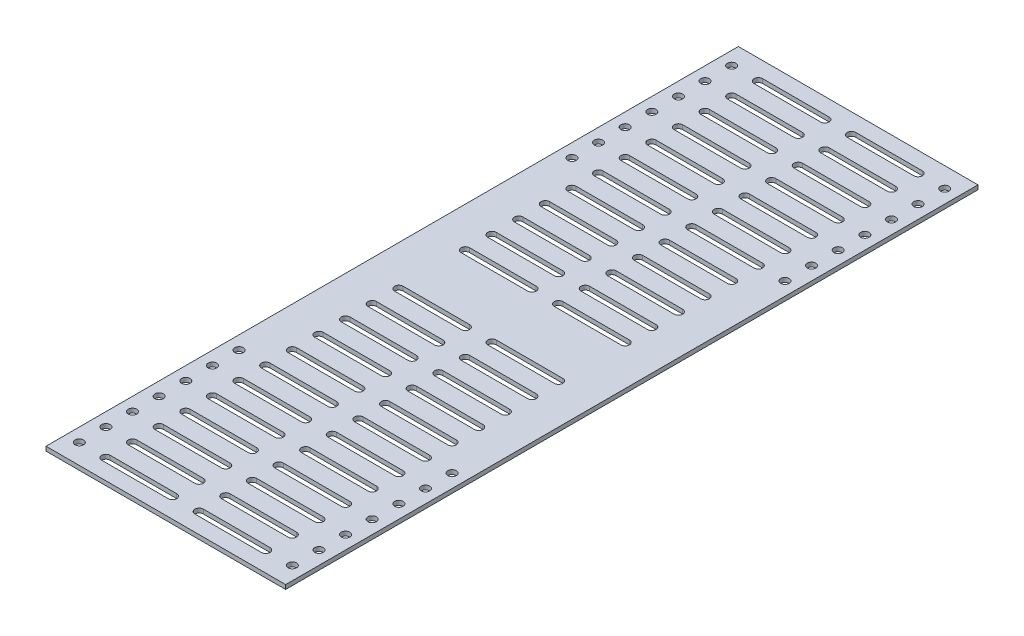
SolidWorks part; units mm, degrees
ref_plane "Front Plane" through (0, 0, 0) normal (0, 0, 1) x (1, 0, 0)
ref_plane "Top Plane" through (0, 0, 0) normal (0, 1, 0) x (1, 0, 0)
ref_plane "Right Plane" through (0, 0, 0) normal (1, 0, 0) x (0, 0, -1)
sketch "Sketch1" plane through (0, 0, 0) normal (0, 1, 0) x (1, 0, 0)
  line L1 (0, 0) -> (90, 0)
  line L2 (0, 0) -> (0, 260)
  line L3 (0, 260) -> (90, 260)
  line L4 (90, 0) -> (90, 260)
  dimension "D1" = 260
  dimension "D2" = 90
extrude "Boss-Extrude1" add sketch "Sketch1" along normal blind 1.6
sketch "Sketch2" plane through (0, 1.6, 0) normal (0, 1, 0) x (1, 0, 0)
  line L0 (45, 260) -> (45, 0) construction
  line L1 (90, 260) -> (0, 260) construction
  line L2 (0, 0) -> (90, 0) construction
  line L3 (5, 252.5) -> (5, 202.5) construction
  line L4 (0, 130) -> (90, 130) construction
  line L5 (0, 260) -> (0, 0) construction
  line L6 (90, 0) -> (90, 260) construction
  line L7 (5, 7.5) -> (5, 57.5) construction
  circle A0 centre (5, 252.5) radius 1.6
  circle A1 centre (85, 252.5) radius 1.6
  circle A2 centre (85, 242.5) radius 1.6
  circle A3 centre (85, 232.5) radius 1.6
  circle A4 centre (85, 222.5) radius 1.6
  circle A5 centre (85, 212.5) radius 1.6
  circle A6 centre (85, 202.5) radius 1.6
  circle A7 centre (5, 242.5) radius 1.6
  circle A8 centre (5, 232.5) radius 1.6
  circle A9 centre (5, 222.5) radius 1.6
  circle A10 centre (5, 212.5) radius 1.6
  circle A11 centre (5, 202.5) radius 1.6
  circle A12 centre (5, 192.5) radius 1.6
  circle A13 centre (85, 192.5) radius 1.6
  circle A14 centre (85, 67.5) radius 1.6
  circle A15 centre (5, 67.5) radius 1.6
  circle A16 centre (5, 57.5) radius 1.6
  circle A17 centre (5, 47.5) radius 1.6
  circle A18 centre (5, 37.5) radius 1.6
  circle A19 centre (5, 27.5) radius 1.6
  circle A20 centre (5, 17.5) radius 1.6
  circle A21 centre (85, 57.5) radius 1.6
  circle A22 centre (85, 47.5) radius 1.6
  circle A23 centre (85, 37.5) radius 1.6
  circle A24 centre (85, 27.5) radius 1.6
  circle A25 centre (85, 17.5) radius 1.6
  circle A26 centre (85, 7.5) radius 1.6
  circle A27 centre (5, 7.5) radius 1.6
  dimension "D1" = 3.2
  dimension "D6" = 10
  dimension "D2" = 40
  dimension "D3" = 7.5
  dimension "D7" = 80
  dimension "D4" = 2
  dimension "D5" = 7
extrude "Cut-Extrude1" cut sketch "Sketch2" against normal through all
sketch "Sketch3" plane through (0, 1.6, 0) normal (0, 1, 0) x (1, 0, 0)
  line L0 (0, 130) -> (90, 130) construction
  line L1 (0, 260) -> (0, 0) construction
  line L2 (90, 0) -> (90, 260) construction
  line L3 (45, 260) -> (45, 0) construction
  line L4 (0, 0) -> (90, 0) construction
  line L21 (15, 252.5) -> (40, 252.5) construction
  line L22 (15, 254.1) -> (40, 254.1)
  line L23 (15, 250.9) -> (40, 250.9)
  line L24 (15, 242.5) -> (40, 242.5) construction
  line L25 (15, 244.1) -> (40, 244.1)
  line L26 (15, 240.9) -> (40, 240.9)
  line L27 (15, 232.5) -> (40, 232.5) construction
  line L28 (15, 234.1) -> (40, 234.1)
  line L29 (15, 230.9) -> (40, 230.9)
  line L30 (15, 222.5) -> (40, 222.5) construction
  line L31 (15, 224.1) -> (40, 224.1)
  line L32 (15, 220.9) -> (40, 220.9)
  line L33 (15, 212.5) -> (40, 212.5) construction
  line L34 (15, 214.1) -> (40, 214.1)
  line L35 (15, 210.9) -> (40, 210.9)
  line L36 (15, 202.5) -> (40, 202.5) construction
  line L37 (15, 204.1) -> (40, 204.1)
  line L38 (15, 200.9) -> (40, 200.9)
  line L39 (15, 192.5) -> (40, 192.5) construction
  line L40 (15, 194.1) -> (40, 194.1)
  line L41 (15, 190.9) -> (40, 190.9)
  line L42 (15, 182.5) -> (40, 182.5) construction
  line L43 (15, 184.1) -> (40, 184.1)
  line L44 (15, 180.9) -> (40, 180.9)
  line L45 (15, 172.5) -> (40, 172.5) construction
  line L46 (15, 174.1) -> (40, 174.1)
  line L47 (15, 170.9) -> (40, 170.9)
  line L48 (15, 162.5) -> (40, 162.5) construction
  line L49 (15, 164.1) -> (40, 164.1)
  line L50 (15, 160.9) -> (40, 160.9)
  line L51 (15, 152.5) -> (40, 152.5) construction
  line L52 (15, 154.1) -> (40, 154.1)
  line L53 (15, 150.9) -> (40, 150.9)
  line L54 (15, 142.5) -> (40, 142.5) construction
  line L55 (15, 144.1) -> (40, 144.1)
  line L56 (15, 140.9) -> (40, 140.9)
  line L57 (15, 7.5) -> (40, 7.5) construction
  line L58 (15, 5.9) -> (40, 5.9)
  line L59 (15, 9.1) -> (40, 9.1)
  line L60 (15, 17.5) -> (40, 17.5) construction
  line L61 (15, 15.9) -> (40, 15.9)
  line L62 (15, 19.1) -> (40, 19.1)
  line L63 (15, 27.5) -> (40, 27.5) construction
  line L64 (15, 25.9) -> (40, 25.9)
  line L65 (15, 29.1) -> (40, 29.1)
  line L66 (15, 37.5) -> (40, 37.5) construction
  line L67 (15, 35.9) -> (40, 35.9)
  line L68 (15, 39.1) -> (40, 39.1)
  line L69 (15, 47.5) -> (40, 47.5) construction
  line L70 (15, 45.9) -> (40, 45.9)
  line L71 (15, 49.1) -> (40, 49.1)
  line L72 (15, 57.5) -> (40, 57.5) construction
  line L73 (15, 55.9) -> (40, 55.9)
  line L74 (15, 59.1) -> (40, 59.1)
  line L75 (15, 67.5) -> (40, 67.5) construction
  line L76 (15, 65.9) -> (40, 65.9)
  line L77 (15, 69.1) -> (40, 69.1)
  line L78 (15, 77.5) -> (40, 77.5) construction
  line L79 (15, 75.9) -> (40, 75.9)
  line L80 (15, 79.1) -> (40, 79.1)
  line L81 (15, 87.5) -> (40, 87.5) construction
  line L82 (15, 85.9) -> (40, 85.9)
  line L83 (15, 89.1) -> (40, 89.1)
  line L84 (15, 97.5) -> (40, 97.5) construction
  line L85 (15, 95.9) -> (40, 95.9)
  line L86 (15, 99.1) -> (40, 99.1)
  line L87 (15, 107.5) -> (40, 107.5) construction
  line L88 (15, 105.9) -> (40, 105.9)
  line L89 (15, 109.1) -> (40, 109.1)
  line L90 (15, 117.5) -> (40, 117.5) construction
  line L91 (15, 115.9) -> (40, 115.9)
  line L92 (15, 119.1) -> (40, 119.1)
  line L93 (75, 252.5) -> (50, 252.5) construction
  line L94 (75, 254.1) -> (50, 254.1)
  line L95 (75, 250.9) -> (50, 250.9)
  line L96 (75, 242.5) -> (50, 242.5) construction
  line L97 (75, 244.1) -> (50, 244.1)
  line L98 (75, 240.9) -> (50, 240.9)
  line L99 (75, 232.5) -> (50, 232.5) construction
  line L100 (75, 234.1) -> (50, 234.1)
  line L101 (75, 230.9) -> (50, 230.9)
  line L102 (75, 222.5) -> (50, 222.5) construction
  line L103 (75, 224.1) -> (50, 224.1)
  line L104 (75, 220.9) -> (50, 220.9)
  line L105 (75, 212.5) -> (50, 212.5) construction
  line L106 (75, 214.1) -> (50, 214.1)
  line L107 (75, 210.9) -> (50, 210.9)
  line L108 (75, 202.5) -> (50, 202.5) construction
  line L109 (75, 204.1) -> (50, 204.1)
  line L110 (75, 200.9) -> (50, 200.9)
  line L111 (75, 192.5) -> (50, 192.5) construction
  line L112 (75, 194.1) -> (50, 194.1)
  line L113 (75, 190.9) -> (50, 190.9)
  line L114 (75, 182.5) -> (50, 182.5) construction
  line L115 (75, 184.1) -> (50, 184.1)
  line L116 (75, 180.9) -> (50, 180.9)
  line L117 (75, 172.5) -> (50, 172.5) construction
  line L118 (75, 174.1) -> (50, 174.1)
  line L119 (75, 170.9) -> (50, 170.9)
  line L120 (75, 162.5) -> (50, 162.5) construction
  line L121 (75, 164.1) -> (50, 164.1)
  line L122 (75, 160.9) -> (50, 160.9)
  line L123 (75, 152.5) -> (50, 152.5) construction
  line L124 (75, 154.1) -> (50, 154.1)
  line L125 (75, 150.9) -> (50, 150.9)
  line L126 (75, 142.5) -> (50, 142.5) construction
  line L127 (75, 144.1) -> (50, 144.1)
  line L128 (75, 140.9) -> (50, 140.9)
  line L129 (75, 7.5) -> (50, 7.5) construction
  line L130 (75, 5.9) -> (50, 5.9)
  line L131 (75, 9.1) -> (50, 9.1)
  line L132 (75, 17.5) -> (50, 17.5) construction
  line L133 (75, 15.9) -> (50, 15.9)
  line L134 (75, 19.1) -> (50, 19.1)
  line L135 (75, 27.5) -> (50, 27.5) construction
  line L136 (75, 25.9) -> (50, 25.9)
  line L137 (75, 29.1) -> (50, 29.1)
  line L138 (75, 37.5) -> (50, 37.5) construction
  line L139 (75, 35.9) -> (50, 35.9)
  line L140 (75, 39.1) -> (50, 39.1)
  line L141 (75, 47.5) -> (50, 47.5) construction
  line L142 (75, 45.9) -> (50, 45.9)
  line L143 (75, 49.1) -> (50, 49.1)
  line L144 (75, 57.5) -> (50, 57.5) construction
  line L145 (75, 55.9) -> (50, 55.9)
  line L146 (75, 59.1) -> (50, 59.1)
  line L147 (75, 67.5) -> (50, 67.5) construction
  line L148 (75, 65.9) -> (50, 65.9)
  line L149 (75, 69.1) -> (50, 69.1)
  line L150 (75, 77.5) -> (50, 77.5) construction
  line L151 (75, 75.9) -> (50, 75.9)
  line L152 (75, 79.1) -> (50, 79.1)
  line L153 (75, 87.5) -> (50, 87.5) construction
  line L154 (75, 85.9) -> (50, 85.9)
  line L155 (75, 89.1) -> (50, 89.1)
  line L156 (75, 97.5) -> (50, 97.5) construction
  line L157 (75, 95.9) -> (50, 95.9)
  line L158 (75, 99.1) -> (50, 99.1)
  line L159 (75, 107.5) -> (50, 107.5) construction
  line L160 (75, 105.9) -> (50, 105.9)
  line L161 (75, 109.1) -> (50, 109.1)
  line L162 (75, 117.5) -> (50, 117.5) construction
  line L163 (75, 115.9) -> (50, 115.9)
  line L164 (75, 119.1) -> (50, 119.1)
  arc A16 (15, 254.1) -> (15, 250.9) centre (15, 252.5) ccw
  arc A17 (40, 250.9) -> (40, 254.1) centre (40, 252.5) ccw
  arc A18 (15, 244.1) -> (15, 240.9) centre (15, 242.5) ccw
  arc A19 (40, 240.9) -> (40, 244.1) centre (40, 242.5) ccw
  arc A20 (15, 234.1) -> (15, 230.9) centre (15, 232.5) ccw
  arc A21 (40, 230.9) -> (40, 234.1) centre (40, 232.5) ccw
  arc A22 (15, 224.1) -> (15, 220.9) centre (15, 222.5) ccw
  arc A23 (40, 220.9) -> (40, 224.1) centre (40, 222.5) ccw
  arc A24 (15, 214.1) -> (15, 210.9) centre (15, 212.5) ccw
  arc A25 (40, 210.9) -> (40, 214.1) centre (40, 212.5) ccw
  arc A26 (15, 204.1) -> (15, 200.9) centre (15, 202.5) ccw
  arc A27 (40, 200.9) -> (40, 204.1) centre (40, 202.5) ccw
  arc A28 (15, 194.1) -> (15, 190.9) centre (15, 192.5) ccw
  arc A29 (40, 190.9) -> (40, 194.1) centre (40, 192.5) ccw
  arc A30 (15, 184.1) -> (15, 180.9) centre (15, 182.5) ccw
  arc A31 (40, 180.9) -> (40, 184.1) centre (40, 182.5) ccw
  arc A32 (15, 174.1) -> (15, 170.9) centre (15, 172.5) ccw
  arc A33 (40, 170.9) -> (40, 174.1) centre (40, 172.5) ccw
  arc A34 (15, 164.1) -> (15, 160.9) centre (15, 162.5) ccw
  arc A35 (40, 160.9) -> (40, 164.1) centre (40, 162.5) ccw
  arc A36 (15, 154.1) -> (15, 150.9) centre (15, 152.5) ccw
  arc A37 (40, 150.9) -> (40, 154.1) centre (40, 152.5) ccw
  arc A38 (15, 144.1) -> (15, 140.9) centre (15, 142.5) ccw
  arc A39 (40, 140.9) -> (40, 144.1) centre (40, 142.5) ccw
  arc A40 (15, 5.9) -> (15, 9.1) centre (15, 7.5) cw
  arc A41 (40, 9.1) -> (40, 5.9) centre (40, 7.5) cw
  arc A42 (15, 15.9) -> (15, 19.1) centre (15, 17.5) cw
  arc A43 (40, 19.1) -> (40, 15.9) centre (40, 17.5) cw
  arc A44 (15, 25.9) -> (15, 29.1) centre (15, 27.5) cw
  arc A45 (40, 29.1) -> (40, 25.9) centre (40, 27.5) cw
  arc A46 (15, 35.9) -> (15, 39.1) centre (15, 37.5) cw
  arc A47 (40, 39.1) -> (40, 35.9) centre (40, 37.5) cw
  arc A48 (15, 45.9) -> (15, 49.1) centre (15, 47.5) cw
  arc A49 (40, 49.1) -> (40, 45.9) centre (40, 47.5) cw
  arc A50 (15, 55.9) -> (15, 59.1) centre (15, 57.5) cw
  arc A51 (40, 59.1) -> (40, 55.9) centre (40, 57.5) cw
  arc A52 (15, 65.9) -> (15, 69.1) centre (15, 67.5) cw
  arc A53 (40, 69.1) -> (40, 65.9) centre (40, 67.5) cw
  arc A54 (15, 75.9) -> (15, 79.1) centre (15, 77.5) cw
  arc A55 (40, 79.1) -> (40, 75.9) centre (40, 77.5) cw
  arc A56 (15, 85.9) -> (15, 89.1) centre (15, 87.5) cw
  arc A57 (40, 89.1) -> (40, 85.9) centre (40, 87.5) cw
  arc A58 (15, 95.9) -> (15, 99.1) centre (15, 97.5) cw
  arc A59 (40, 99.1) -> (40, 95.9) centre (40, 97.5) cw
  arc A60 (15, 105.9) -> (15, 109.1) centre (15, 107.5) cw
  arc A61 (40, 109.1) -> (40, 105.9) centre (40, 107.5) cw
  arc A62 (15, 115.9) -> (15, 119.1) centre (15, 117.5) cw
  arc A63 (40, 119.1) -> (40, 115.9) centre (40, 117.5) cw
  arc A64 (75, 254.1) -> (75, 250.9) centre (75, 252.5) cw
  arc A65 (50, 250.9) -> (50, 254.1) centre (50, 252.5) cw
  arc A66 (75, 244.1) -> (75, 240.9) centre (75, 242.5) cw
  arc A67 (50, 240.9) -> (50, 244.1) centre (50, 242.5) cw
  arc A68 (75, 234.1) -> (75, 230.9) centre (75, 232.5) cw
  arc A69 (50, 230.9) -> (50, 234.1) centre (50, 232.5) cw
  arc A70 (75, 224.1) -> (75, 220.9) centre (75, 222.5) cw
  arc A71 (50, 220.9) -> (50, 224.1) centre (50, 222.5) cw
  arc A72 (75, 214.1) -> (75, 210.9) centre (75, 212.5) cw
  arc A73 (50, 210.9) -> (50, 214.1) centre (50, 212.5) cw
  arc A74 (75, 204.1) -> (75, 200.9) centre (75, 202.5) cw
  arc A75 (50, 200.9) -> (50, 204.1) centre (50, 202.5) cw
  arc A76 (75, 194.1) -> (75, 190.9) centre (75, 192.5) cw
  arc A77 (50, 190.9) -> (50, 194.1) centre (50, 192.5) cw
  arc A78 (75, 184.1) -> (75, 180.9) centre (75, 182.5) cw
  arc A79 (50, 180.9) -> (50, 184.1) centre (50, 182.5) cw
  arc A80 (75, 174.1) -> (75, 170.9) centre (75, 172.5) cw
  arc A81 (50, 170.9) -> (50, 174.1) centre (50, 172.5) cw
  arc A82 (75, 164.1) -> (75, 160.9) centre (75, 162.5) cw
  arc A83 (50, 160.9) -> (50, 164.1) centre (50, 162.5) cw
  arc A84 (75, 154.1) -> (75, 150.9) centre (75, 152.5) cw
  arc A85 (50, 150.9) -> (50, 154.1) centre (50, 152.5) cw
  arc A86 (75, 144.1) -> (75, 140.9) centre (75, 142.5) cw
  arc A87 (50, 140.9) -> (50, 144.1) centre (50, 142.5) cw
  arc A88 (75, 5.9) -> (75, 9.1) centre (75, 7.5) ccw
  arc A89 (50, 9.1) -> (50, 5.9) centre (50, 7.5) ccw
  arc A90 (75, 15.9) -> (75, 19.1) centre (75, 17.5) ccw
  arc A91 (50, 19.1) -> (50, 15.9) centre (50, 17.5) ccw
  arc A92 (75, 25.9) -> (75, 29.1) centre (75, 27.5) ccw
  arc A93 (50, 29.1) -> (50, 25.9) centre (50, 27.5) ccw
  arc A94 (75, 35.9) -> (75, 39.1) centre (75, 37.5) ccw
  arc A95 (50, 39.1) -> (50, 35.9) centre (50, 37.5) ccw
  arc A96 (75, 45.9) -> (75, 49.1) centre (75, 47.5) ccw
  arc A97 (50, 49.1) -> (50, 45.9) centre (50, 47.5) ccw
  arc A98 (75, 55.9) -> (75, 59.1) centre (75, 57.5) ccw
  arc A99 (50, 59.1) -> (50, 55.9) centre (50, 57.5) ccw
  arc A100 (75, 65.9) -> (75, 69.1) centre (75, 67.5) ccw
  arc A101 (50, 69.1) -> (50, 65.9) centre (50, 67.5) ccw
  arc A102 (75, 75.9) -> (75, 79.1) centre (75, 77.5) ccw
  arc A103 (50, 79.1) -> (50, 75.9) centre (50, 77.5) ccw
  arc A104 (75, 85.9) -> (75, 89.1) centre (75, 87.5) ccw
  arc A105 (50, 89.1) -> (50, 85.9) centre (50, 87.5) ccw
  arc A106 (75, 95.9) -> (75, 99.1) centre (75, 97.5) ccw
  arc A107 (50, 99.1) -> (50, 95.9) centre (50, 97.5) ccw
  arc A108 (75, 105.9) -> (75, 109.1) centre (75, 107.5) ccw
  arc A109 (50, 109.1) -> (50, 105.9) centre (50, 107.5) ccw
  arc A110 (75, 115.9) -> (75, 119.1) centre (75, 117.5) ccw
  arc A111 (50, 119.1) -> (50, 115.9) centre (50, 117.5) ccw
  point P11 (45, 130)
  point P13 (27.5, 252.5)
  point P18 (5, 252.5)
  point P23 (27.5, 242.5)
  point P30 (27.5, 232.5)
  point P37 (27.5, 222.5)
  point P44 (27.5, 212.5)
  point P51 (27.5, 202.5)
  point P58 (27.5, 192.5)
  point P66 (27.5, 182.5)
  point P73 (27.5, 172.5)
  point P80 (27.5, 162.5)
  point P87 (27.5, 152.5)
  point P94 (27.5, 142.5)
  point P99 (27.5, 7.5)
  point P106 (27.5, 17.5)
  point P113 (27.5, 27.5)
  point P120 (27.5, 37.5)
  point P127 (27.5, 47.5)
  point P134 (27.5, 57.5)
  point P141 (27.5, 67.5)
  point P148 (27.5, 77.5)
  point P155 (27.5, 87.5)
  point P162 (27.5, 97.5)
  point P169 (27.5, 107.5)
  point P176 (27.5, 117.5)
  point P191 (62.5, 252.5)
  point P198 (62.5, 242.5)
  point P205 (62.5, 232.5)
  point P212 (62.5, 222.5)
  point P219 (62.5, 212.5)
  point P226 (62.5, 202.5)
  point P233 (62.5, 192.5)
  point P240 (62.5, 182.5)
  point P247 (62.5, 172.5)
  point P254 (62.5, 162.5)
  point P261 (62.5, 152.5)
  point P268 (62.5, 142.5)
  point P275 (62.5, 7.5)
  point P282 (62.5, 17.5)
  point P289 (62.5, 27.5)
  point P296 (62.5, 37.5)
  point P303 (62.5, 47.5)
  point P310 (62.5, 57.5)
  point P317 (62.5, 67.5)
  point P324 (62.5, 77.5)
  point P331 (62.5, 87.5)
  point P338 (62.5, 97.5)
  point P345 (62.5, 107.5)
  point P352 (62.5, 117.5)
  point P357 (85, 252.5)
  dimension "D4" = 10
  dimension "D3" = 15
  dimension "D1" = 3.2
  dimension "D2" = 12
  dimension "D5" = 5
extrude "Cut-Extrude2" cut sketch "Sketch3" against normal blind 10
